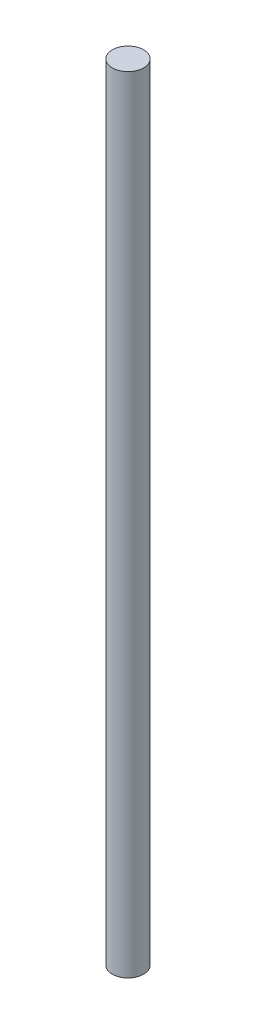
SolidWorks part; units mm, degrees
material "Д16Т ГОСТ 4784-97"
ref_plane "Front Plane" through (0, 0, 0) normal (0, 0, 1) x (1, 0, 0)
ref_plane "Top Plane" through (0, 0, 0) normal (0, 1, 0) x (1, 0, 0)
ref_plane "Right Plane" through (0, 0, 0) normal (1, 0, 0) x (0, 0, -1)
sketch "Sketch2" plane through (0, 0, 0) normal (0, 0, 1) x (1, 0, 0)
  line L0 (0, 256.5994) -> (0, -253.7156) construction
  line L4 (-8, -200) -> (0, -200)
  line L5 (-151.2934, 0) -> (177.5821, 0) construction
  line L8 (-8, 200) -> (0, 200)
  line L9 (0, -200) -> (0, 200)
  line L12 (-8, -200) -> (-8, 200)
  dimension "D1" = 8
  dimension "D2" = 400
revolve "Revolve1" add sketch "Sketch2" angle 360 about L0
